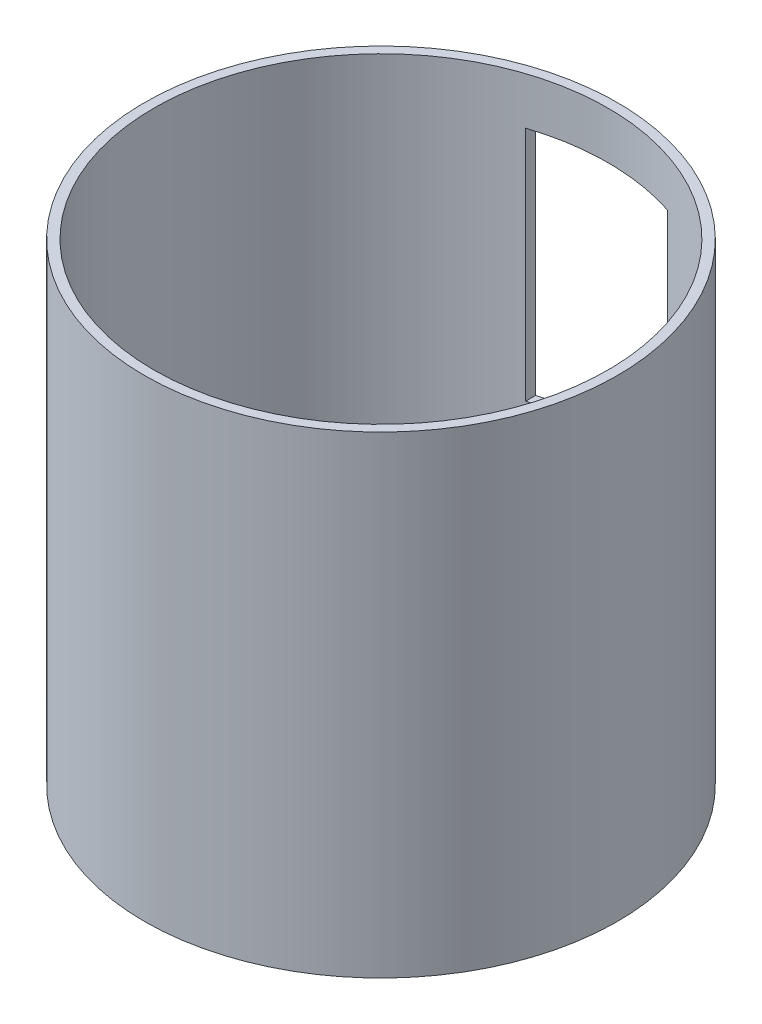
SolidWorks part; units mm, degrees
ref_plane "Front Plane" through (0, 0, 0) normal (0, 0, 1) x (1, 0, 0)
ref_plane "Top Plane" through (0, 0, 0) normal (0, 1, 0) x (1, 0, 0)
ref_plane "Right Plane" through (0, 0, 0) normal (1, 0, 0) x (0, 0, -1)
sketch "Sketch1" plane through (0, 0, 0) normal (0, 1, 0) x (1, 0, 0)
  circle A0 centre (0, 0) radius 2500
  dimension "D1" = 5000
extrude "Boss-Extrude1" add sketch "Sketch1" along normal blind 5000
sketch "Sketch2" plane through (0, 0, 0) normal (0, -1, 0) x (1, 0, 0)
  circle A0 centre (0, 0) radius 2000
  dimension "D1" = 4000
extrude "Cut-Extrude1" cut sketch "Sketch2" against normal blind 500
sketch "Sketch3" plane through (0, 5000, 0) normal (0, 1, 0) x (1, 0, 0)
  circle A0 centre (0, 0) radius 2400
  dimension "D1" = 4800
extrude "Cut-Extrude2" cut sketch "Sketch3" against normal blind 4420
sketch "Sketch4" plane through (0, 0, 0) normal (0, 0, 1) x (1, 0, 0)
  line L1 (-750, -4500) -> (750, -4500)
  line L2 (-750, -4500) -> (-750, 4500)
  line L3 (-750, 4500) -> (750, 4500)
  line L4 (750, -4500) -> (750, 4500)
  line L5 (-750, -4500) -> (750, 4500) construction
  line L6 (-750, 4500) -> (750, -4500) construction
  line L7 (750, 4500) -> (-750, 4500)
  line L8 (750, 4500) -> (750, 2000)
  line L9 (750, 2000) -> (-750, 2000)
  line L10 (-750, 4500) -> (-750, 2000)
  point P0 (0, 0)
  dimension "D1" = 9000
  dimension "D2" = 1500
  dimension "D3" = 2500
extrude "Cut-Extrude3" cut sketch "Sketch4" against normal blind 4420 contours L9 L4 L3 L2
